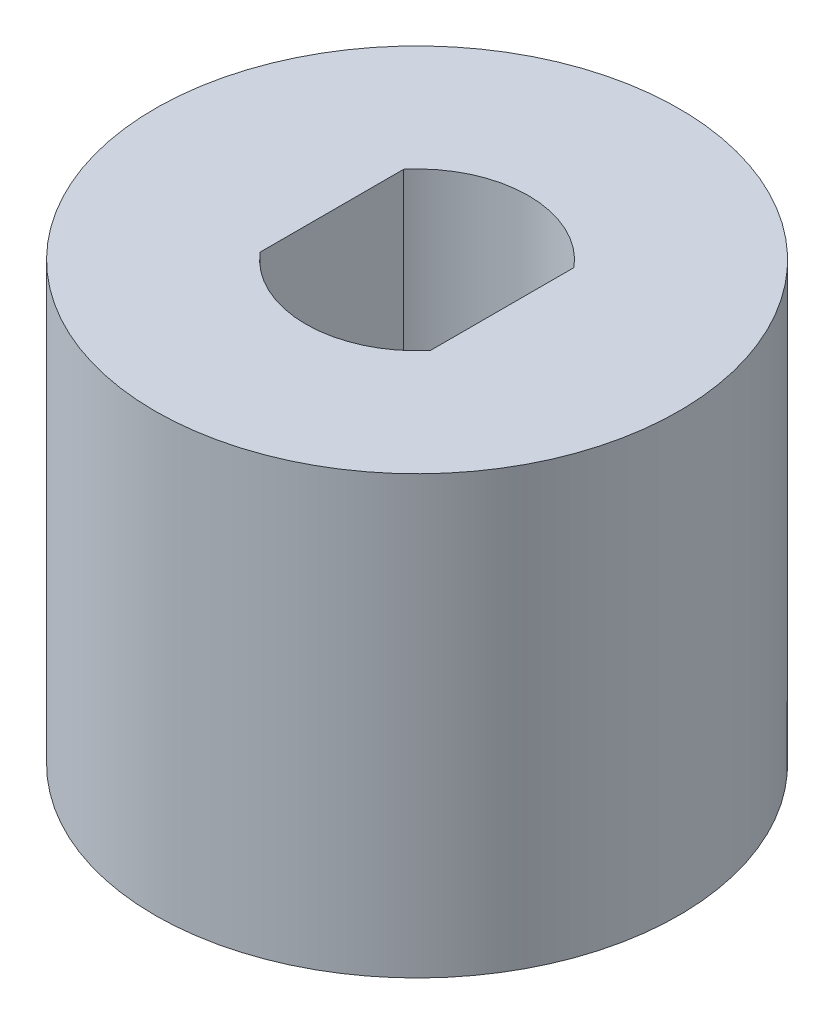
SolidWorks part; units mm, degrees
ref_plane "Front Plane" through (0, 0, 0) normal (0, 0, 1) x (1, 0, 0)
ref_plane "Top Plane" through (0, 0, 0) normal (0, 1, 0) x (1, 0, 0)
ref_plane "Right Plane" through (0, 0, 0) normal (1, 0, 0) x (0, 0, -1)
sketch "Sketch1" plane through (0, 0, 0) normal (0, 1, 0) x (1, 0, 0)
  circle A0 centre (0, 0) radius 6
  dimension "D1" = 12
extrude "Boss-Extrude1" add sketch "Sketch1" along normal blind 10
sketch "Sketch2" plane through (0, 10, 0) normal (0, 1, 0) x (1, 0, 0)
  line L0 (0, 0) -> (0, 2.55) construction
  line L1 (0, 2.55) -> (-2.75, 0) construction
  line L2 (-2.75, 0) -> (2.75, 0) construction
  line L3 (1.95, -1.6432) -> (1.95, 1.6432)
  line L4 (-1.95, -1.6432) -> (-1.95, 1.6432)
  arc A0 (-1.95, -1.6432) -> (1.95, -1.6432) centre (0, 0) ccw
  arc A1 (1.95, 1.6432) -> (-1.95, 1.6432) centre (0, 0) ccw
  point P9 (1.95, 0)
  dimension "D1" = 5.1
  dimension "D2" = 1.95
sketch "Sketch3" plane through (0, 0, 0) normal (0, -1, 0) x (1, 0, 0)
  line L0 (0, 0) -> (3.5, 0) construction
  line L1 (3.5, 0) -> (0, 3.525) construction
  line L2 (0, 3.525) -> (0, -3.525) construction
  line L3 (2.5, -2.4851) -> (2.5, 2.4851)
  line L4 (-2.5, -2.4851) -> (-2.5, 2.4851)
  arc A0 (-2.5, -2.4851) -> (2.5, -2.4851) centre (0, 0) ccw
  arc A1 (2.5, 2.4851) -> (-2.5, 2.4851) centre (0, 0) ccw
  point P9 (2.5, 0)
  dimension "D1" = 7.05
  dimension "D2" = 2.5
extrude "Cut-Extrude1" cut sketch "Sketch3" against normal blind 6
extrude "Cut-Extrude2" cut sketch "Sketch2" against normal blind 5
